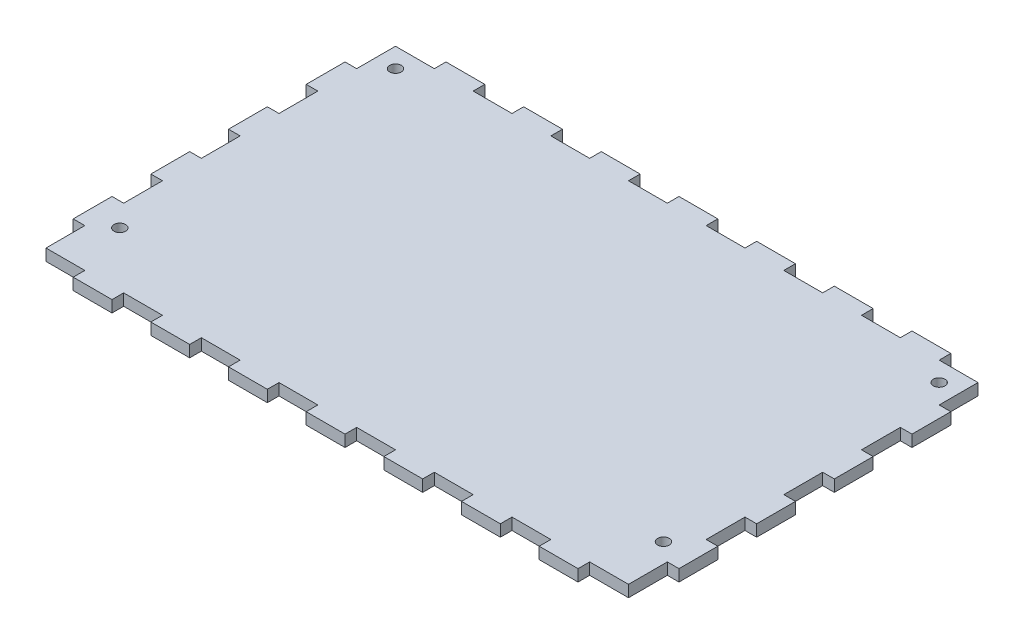
SolidWorks part; units mm, degrees
ref_plane "Front Plane" through (0, 0, 0) normal (0, 0, 1) x (1, 0, 0)
ref_plane "Top Plane" through (0, 0, 0) normal (0, 1, 0) x (1, 0, 0)
ref_plane "Right Plane" through (0, 0, 0) normal (1, 0, 0) x (0, 0, -1)
sketch "Sketch1" plane through (0, 0, 0) normal (0, 1, 0) x (1, 0, 0)
  line L0 (15, 45) -> (25, 48) construction
  line L1 (-76.5, 46.5) -> (76.5, 46.5) construction
  line L2 (-76.5, 46.5) -> (-76.5, -46.5) construction
  line L3 (-76.5, -46.5) -> (76.5, -46.5) construction
  line L4 (76.5, 46.5) -> (76.5, -46.5) construction
  line L5 (-76.5, 46.5) -> (76.5, -46.5) construction
  line L6 (-76.5, -46.5) -> (76.5, 46.5) construction
  line L7 (-5, 48) -> (5, 48)
  line L8 (-5, 48) -> (-5, 45)
  line L9 (-5, 45) -> (5, 45) construction
  line L10 (5, 48) -> (5, 45)
  line L11 (-5, 48) -> (5, 45) construction
  line L12 (-5, 45) -> (5, 48) construction
  line L13 (15, 45) -> (25, 45) construction
  line L14 (15, 48) -> (25, 45) construction
  line L15 (25, 48) -> (25, 45)
  line L16 (15, 48) -> (25, 48)
  line L17 (15, 48) -> (15, 45)
  line L18 (35, 45) -> (45, 48) construction
  line L19 (35, 45) -> (45, 45) construction
  line L20 (35, 48) -> (45, 45) construction
  line L21 (45, 48) -> (45, 45)
  line L22 (35, 48) -> (45, 48)
  line L23 (35, 48) -> (35, 45)
  line L24 (55, 45) -> (65, 48) construction
  line L25 (55, 45) -> (65, 45) construction
  line L26 (55, 48) -> (65, 45) construction
  line L27 (65, 48) -> (65, 45)
  line L28 (55, 48) -> (65, 48)
  line L29 (55, 48) -> (55, 45)
  line L30 (-25, 45) -> (-15, 48) construction
  line L31 (-25, 45) -> (-15, 45) construction
  line L32 (-25, 48) -> (-15, 45) construction
  line L33 (-15, 48) -> (-15, 45)
  line L34 (-25, 48) -> (-15, 48)
  line L35 (-25, 48) -> (-25, 45)
  line L36 (-45, 45) -> (-35, 48) construction
  line L37 (-45, 45) -> (-35, 45) construction
  line L38 (-45, 48) -> (-35, 45) construction
  line L39 (-35, 48) -> (-35, 45)
  line L40 (-45, 48) -> (-35, 48)
  line L41 (-45, 48) -> (-45, 45)
  line L42 (-65, 45) -> (-55, 48) construction
  line L43 (-65, 45) -> (-55, 45) construction
  line L44 (-65, 48) -> (-55, 45) construction
  line L45 (-55, 48) -> (-55, 45)
  line L46 (-65, 48) -> (-55, 48)
  line L47 (-65, 48) -> (-65, 45)
  line L48 (-55, 45) -> (-45, 45)
  line L49 (-35, 45) -> (-25, 45)
  line L50 (-15, 45) -> (-5, 45)
  line L51 (5, 45) -> (15, 45)
  line L52 (25, 45) -> (35, 45)
  line L53 (45, 45) -> (55, 45)
  line L54 (55, 48) -> (45, 48) construction
  line L55 (0, 0) -> (9.7796, 0) construction
  line L56 (0, 0) -> (0, 12.2502) construction
  line L57 (65, -48) -> (65, -45)
  line L58 (55, -48) -> (65, -48)
  line L59 (55, -48) -> (55, -45)
  line L60 (45, -45) -> (55, -45)
  line L61 (45, -48) -> (45, -45)
  line L62 (35, -48) -> (45, -48)
  line L63 (35, -48) -> (35, -45)
  line L64 (25, -45) -> (35, -45)
  line L65 (25, -48) -> (25, -45)
  line L66 (15, -48) -> (25, -48)
  line L67 (15, -48) -> (15, -45)
  line L68 (5, -45) -> (15, -45)
  line L69 (5, -48) -> (5, -45)
  line L70 (-5, -48) -> (5, -48)
  line L71 (-5, -48) -> (-5, -45)
  line L72 (-15, -45) -> (-5, -45)
  line L73 (-15, -48) -> (-15, -45)
  line L74 (-25, -48) -> (-15, -48)
  line L75 (-25, -48) -> (-25, -45)
  line L76 (-35, -45) -> (-25, -45)
  line L77 (-35, -48) -> (-35, -45)
  line L78 (-45, -48) -> (-35, -48)
  line L79 (-45, -48) -> (-45, -45)
  line L80 (-55, -45) -> (-45, -45)
  line L81 (-55, -48) -> (-55, -45)
  line L82 (-65, -48) -> (-65, -45)
  line L83 (-65, -48) -> (-55, -48)
  line L84 (-65, 45) -> (-75, 45)
  line L89 (-75, 45) -> (-75, 35)
  line L90 (-75, 25) -> (-75, 15)
  line L91 (-78, 25) -> (-75, 25)
  line L92 (-78, 25) -> (-78, 35)
  line L93 (-78, 35) -> (-75, 35)
  line L94 (-75, 25) -> (-75, 35) construction
  line L95 (-78, 25) -> (-75, 35) construction
  line L96 (-78, 35) -> (-75, 25) construction
  line L97 (-78, 5) -> (-75, 5)
  line L98 (-78, 5) -> (-75, 15) construction
  line L99 (-78, 5) -> (-78, 15)
  line L100 (-78, 15) -> (-75, 5) construction
  line L101 (-78, 15) -> (-75, 15)
  line L102 (-75, 5) -> (-75, 15) construction
  line L103 (-78, -15) -> (-75, -15)
  line L104 (-78, -15) -> (-75, -5) construction
  line L105 (-78, -15) -> (-78, -5)
  line L106 (-78, -5) -> (-75, -15) construction
  line L107 (-78, -5) -> (-75, -5)
  line L108 (-75, -15) -> (-75, -5) construction
  line L109 (-78, -35) -> (-75, -35)
  line L110 (-78, -35) -> (-75, -25) construction
  line L111 (-78, -35) -> (-78, -25)
  line L112 (-78, -25) -> (-75, -35) construction
  line L113 (-78, -25) -> (-75, -25)
  line L114 (-75, -35) -> (-75, -25) construction
  line L115 (-75, 5) -> (-75, -5)
  line L116 (-75, -15) -> (-75, -25)
  line L117 (-75, -35) -> (-75, -45)
  line L118 (-75, -45) -> (-65, -45)
  line L119 (65, 45) -> (75, 45)
  line L120 (65, -45) -> (75, -45)
  line L121 (75, -35) -> (75, -45)
  line L122 (78, -35) -> (75, -35)
  line L123 (78, -35) -> (78, -25)
  line L124 (78, -25) -> (75, -25)
  line L125 (75, -15) -> (75, -25)
  line L126 (78, -15) -> (75, -15)
  line L127 (78, -15) -> (78, -5)
  line L128 (78, -5) -> (75, -5)
  line L129 (75, 5) -> (75, -5)
  line L130 (78, 5) -> (75, 5)
  line L131 (78, 5) -> (78, 15)
  line L132 (78, 15) -> (75, 15)
  line L133 (75, 25) -> (75, 15)
  line L134 (78, 25) -> (75, 25)
  line L135 (78, 25) -> (78, 35)
  line L136 (78, 35) -> (75, 35)
  line L137 (75, 45) -> (75, 35)
  point P0 (0, 0)
  point P6 (0, 46.5)
  point P66 (-76.5, 30)
  dimension "D1" = 153
  dimension "D2" = 93
  dimension "D3" = 10
  dimension "D4" = 3
  dimension "D5" = 4
  dimension "D7" = 10
  dimension "D8" = 10
  dimension "D9" = 10
  dimension "D10" = 10
  dimension "D11" = 10
  dimension "D12" = 10
  dimension "D6" = 4
  dimension "D13" = 4
extrude "Boss-Extrude1" add sketch "Sketch1" along normal blind 3
sketch "Sketch2" plane through (0, 3, 0) normal (0, 1, 0) x (1, 0, 0)
  line L0 (0, 0) -> (0, 17.6247) construction
  line L1 (0, 0) -> (15.2388, 0) construction
  line L2 (75, 45) -> (65, 45) construction
  line L3 (70, 40) -> (70, -31) construction
  circle A0 centre (70, 40) radius 1.5
  circle A4 centre (70, -31) radius 1.5
  circle A5 centre (-70, 40) radius 1.5
  circle A6 centre (-70, -31) radius 1.5
  dimension "D3" = 5
  dimension "D2" = 3
  dimension "D5" = 3
  dimension "D1" = 70
  dimension "D4" = 71
extrude "Cut-Extrude1" cut sketch "Sketch2" against normal blind 3
